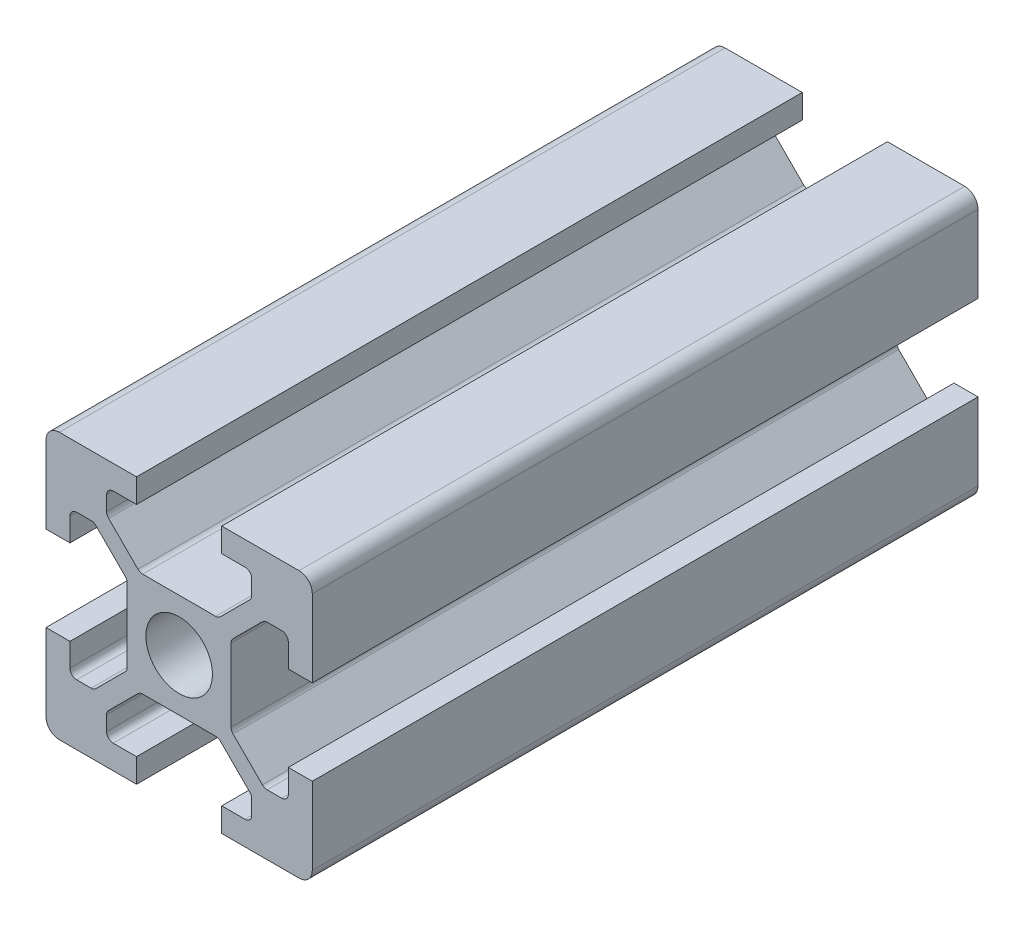
SolidWorks part; units mm, degrees
material "1060 Alloy"
ref_plane "Front Plane" through (0, 0, 0) normal (0, 0, 1) x (1, 0, 0)
ref_plane "Top Plane" through (0, 0, 0) normal (0, 1, 0) x (1, 0, 0)
ref_plane "Right Plane" through (0, 0, 0) normal (1, 0, 0) x (0, 0, -1)
sketch "Sketch1" plane through (0, 0, 0) normal (0, 0, 1) x (1, 0, 0)
  line L0 (20, 0) -> (-8.059, 28.059) construction
  line L1 (0, 0) -> (6.8, 0)
  line L2 (0, 0) -> (0, 6.8)
  line L3 (0, 20) -> (6.8, 20)
  line L4 (20, 0) -> (20, 6.8)
  line L5 (6.8, 20) -> (6.8, 18.2)
  line L6 (20, 20) -> (8.2322, 8.2322) construction
  line L7 (12.95, 6.1) -> (7.05, 6.1)
  line L8 (13.9, 7.05) -> (13.9, 12.95)
  line L9 (12.95, 13.9) -> (7.05, 13.9)
  line L10 (6.1, 7.05) -> (6.1, 12.95)
  line L11 (13.9, 6.1) -> (6.1, 13.9) construction
  line L12 (13.9, 13.9) -> (6.1, 6.1) construction
  line L13 (4.55, 16.4) -> (7.05, 13.9)
  line L14 (13.2, 18.2) -> (13.2, 20)
  line L15 (1.8, 6.8) -> (0, 6.8)
  line L16 (0, 13.2) -> (0, 20)
  line L17 (0, 13.2) -> (1.8, 13.2)
  line L18 (10, 10) -> (10, 13.9) construction
  line L19 (16.4, 4.55) -> (13.9, 7.05)
  line L20 (4.55, 16.4) -> (4.55, 18.2)
  line L21 (4.55, 18.2) -> (6.8, 18.2)
  line L22 (13.2, 18.2) -> (15.45, 18.2)
  line L23 (15.45, 18.2) -> (15.45, 16.4)
  line L24 (15.45, 16.4) -> (12.95, 13.9)
  line L25 (16.4, 4.55) -> (18.2, 4.55)
  line L26 (18.2, 4.55) -> (18.2, 6.8)
  line L27 (20, 6.8) -> (18.2, 6.8)
  line L28 (18.2, 13.2) -> (20, 13.2)
  line L29 (18.2, 13.2) -> (18.2, 15.45)
  line L30 (18.2, 15.45) -> (16.4, 15.45)
  line L31 (16.4, 15.45) -> (13.9, 12.95)
  line L32 (1.8, 4.55) -> (3.6, 4.55)
  line L33 (3.6, 15.45) -> (6.1, 12.95)
  line L34 (3.6, 15.45) -> (1.8, 15.45)
  line L35 (1.8, 15.45) -> (1.8, 13.2)
  line L36 (0, 13.2) -> (1.8, 13.2)
  line L37 (1.8, 6.8) -> (0, 6.8)
  line L38 (3.6, 4.55) -> (6.1, 7.05)
  line L39 (1.8, 6.8) -> (1.8, 4.55)
  line L40 (15.45, 3.6) -> (12.95, 6.1)
  line L41 (4.55, 3.6) -> (7.05, 6.1)
  line L42 (4.55, 1.8) -> (4.55, 3.6)
  line L43 (6.8, 1.8) -> (4.55, 1.8)
  line L44 (6.8, 1.8) -> (6.8, 0)
  line L45 (15.45, 3.6) -> (15.45, 1.8)
  line L46 (15.45, 1.8) -> (13.2, 1.8)
  line L47 (13.2, 0) -> (13.2, 1.8)
  line L48 (13.2, 20) -> (20, 20)
  line L49 (20, 13.2) -> (20, 20)
  line L50 (13.2, 0) -> (20, 0)
  line L51 (6.1, 6.1) -> (-5.5045, -5.5045) construction
  circle A0 centre (10, 10) radius 2.5
  point P25 (10, 16.4)
  point P39 (13.2, 19.1)
  point P46 (0.9, 6.8)
  dimension "D3" = 5
  dimension "D2" = 20
  dimension "D4" = 7.8
  dimension "D5" = 7.8
  dimension "D6" = 6.8
  dimension "D7" = 6.8
  dimension "D8" = 1.8
  dimension "D9" = 10.9
  dimension "D10" = 1.8
  dimension "D11" = 10.9
  dimension "D12" = 20
extrude "Boss-Extrude1" add sketch "Sketch1" along normal mid plane 50 contours L47 L50 L4 L27 L26 L25 L19 L8 L31 L30 L29 L28 L49 L48 L14 L22 L23 L24 L9 L13 L20 L21 L5 L3 L16 L17 L35 L34 L33 L10 L38 L32 L39 L15 L2 L1 L44 L43 L42 L41 L7 L40 L45 L46 A0
fillet "Fillet1" radius 1 4 edges at (20, 20, 0) (20, 0, 0) (0, 0, 0) (0, 20, 0)
fillet "Fillet2" radius 0.5 6 edges at (4.55, 18.2, 0) (4.55, 16.4, 0) (7.05, 13.9, 0) (15.45, 18.2, 0) (15.45, 16.4, 0) (12.95, 13.9, 0)
fillet "Fillet3" radius 0.5 6 edges at (18.2, 15.45, 0) (16.4, 15.45, 0) (13.9, 12.95, 0) (18.2, 4.55, 0) (13.9, 7.05, 0) (16.4, 4.55, 0)
fillet "Fillet4" radius 0.5 6 edges at (1.8, 15.45, 0) (3.6, 15.45, 0) (6.1, 12.95, 0) (3.6, 4.55, 0) (1.8, 4.55, 0) (6.1, 7.05, 0)
fillet "Fillet5" radius 0.5 6 edges at (7.05, 6.1, 0) (4.55, 3.6, 0) (4.55, 1.8, 0) (15.45, 1.8, 0) (15.45, 3.6, 0) (12.95, 6.1, 0)
